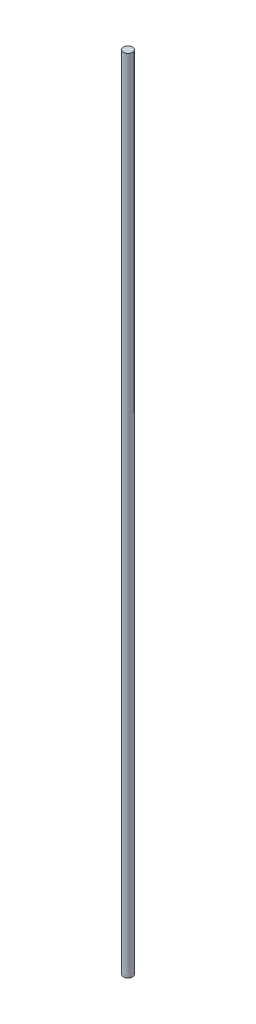
SolidWorks part; units mm, degrees
ref_plane "Front Plane" through (0, 0, 0) normal (0, 0, 1) x (1, 0, 0)
ref_plane "Top Plane" through (0, 0, 0) normal (0, 1, 0) x (1, 0, 0)
ref_plane "Right Plane" through (0, 0, 0) normal (1, 0, 0) x (0, 0, -1)
sketch "Sketch2" plane through (0, 0, 0) normal (0, 1, 0) x (1, 0, 0)
  circle A0 centre (0, 0) radius 1.5
  dimension "D1" = 3
extrude "Boss-Extrude1" add sketch "Sketch2" along normal blind 265
